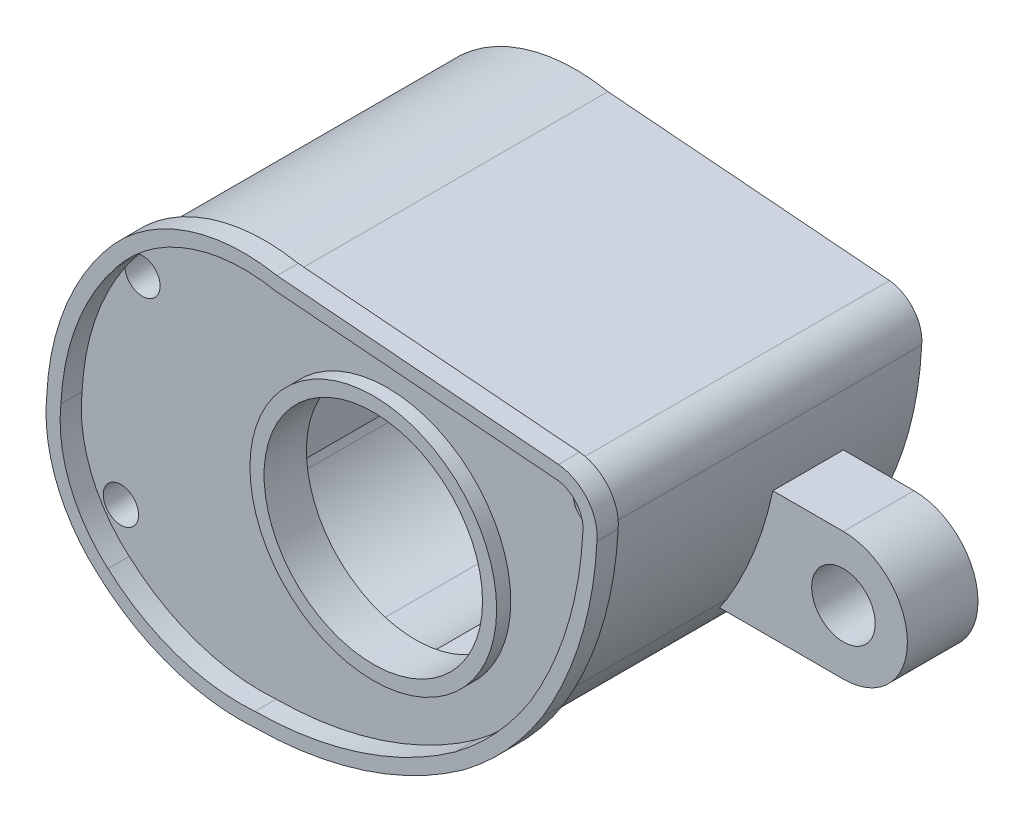
SolidWorks part; units mm, degrees
ref_plane "Front Plane" through (0, 0, 0) normal (0, 0, 1) x (1, 0, 0)
ref_plane "Top Plane" through (0, 0, 0) normal (0, 1, 0) x (1, 0, 0)
ref_plane "Right Plane" through (0, 0, 0) normal (1, 0, 0) x (0, 0, -1)
sketch "Sketch5" plane through (0, 0, 0) normal (0, 0, 1) x (1, 0, 0)
  line L0 (32.2567, 28.3094) -> (-7.6439, 31.5413)
  arc A0 (-7.6439, 31.5413) -> (-31.2267, 22.5712) centre (-12.2121, 8.0664) ccw
  arc A1 (-31.2267, 22.5712) -> (-39.1267, 1.5854) centre (-2.4724, -0.2331) ccw
  arc A2 (-39.1267, 1.5854) -> (-32.1216, -16.1277) centre (-18.7412, -0.5944) ccw
  arc A3 (-32.1216, -16.1277) -> (-10.5935, -23.4924) centre (-12.7582, 5.3271) ccw
  arc A4 (-10.5935, -23.4924) -> (18.3058, -14.101) centre (-11.0051, 26.9339) ccw
  arc A5 (18.3058, -14.101) -> (29.2221, -2.2809) centre (-8.5159, 21.6209) ccw
  arc A6 (29.2221, -2.2809) -> (36.8072, 22.6664) centre (-16.6755, 25.3008) ccw
  arc A7 (36.8072, 22.6664) -> (32.2567, 28.3094) centre (31.7105, 23.2127) ccw
  circle A8 centre (5.125, 6.1357) radius 15.4733
extrude "Boss-Extrude2" add sketch "Sketch5" along normal blind 44
sketch "Sketch12" plane through (0, 0, 44) normal (0, 0, 1) x (1, 0, 0)
  circle A3 centre (5.125, 6.1357) radius 15.4733
  circle A4 centre (5.125, 6.1357) radius 15.4733
  dimension "D1" = 0
extrude "Extrude-Thin3" add sketch "Sketch12" along normal blind 2 thin
sketch "Sketch16" plane through (0, 0, 0) normal (0, 0, -1) x (-1, 0, 0)
  line L43 (22.1955, 22.9487) -> (21.1955, 24.9487)
  line L44 (22.1955, 20.9487) -> (22.1955, 22.9487)
  line L45 (22.5955, 14.9487) -> (22.1955, 20.9487)
  line L46 (23.3698, 11.8701) -> (22.5955, 14.9487)
  line L47 (24.1112, 7.8732) -> (23.3698, 11.8701)
  line L48 (24.5555, 3.8743) -> (24.1112, 7.8732)
  line L49 (25.5954, -10.0513) -> (24.5555, 3.8743)
  line L50 (-15.5531, -13.0513) -> (-4.0536, -13.0513)
  line L51 (-25.5527, 9.9487) -> (-15.5531, -13.0513)
  line L52 (-29.6312, 9.9487) -> (-25.5527, 9.9487)
  line L53 (-31.5525, 24.9487) -> (-31.5525, 12.6882)
  line L54 (21.1955, 24.9487) -> (-31.5525, 24.9487)
  arc A12 (25.1918, -11.0133) -> (25.5954, -10.0513) centre (19.3606, -8.0014) ccw
  arc A13 (25.1918, -11.0133) -> (10.4852, -20.0276) centre (10.3895, -3.3677) cw
  arc A14 (-4.0536, -13.0513) -> (10.4852, -20.0276) centre (8.991, -4.5038) ccw
  arc A15 (-31.5525, 12.6882) -> (-29.6312, 9.9487) centre (-38.2464, 5.95) cw
extrude "Cut-Extrude1" cut sketch "Sketch16" against normal blind 40
sketch "Sketch20" plane through (0, 0, 44) normal (0, 0, 1) x (1, 0, 0)
  circle A0 centre (33.9607, 23.4641) radius 2.5
  circle A1 centre (-29.5785, 19.9554) radius 2.5
  circle A2 centre (-32.6296, -9.6403) radius 2.5
  point P2 (33.9607, 23.4641)
extrude "Cut-Extrude4" cut sketch "Sketch20" against normal blind 5
sketch "Sketch21" plane through (0, 0, 39) normal (0, 0, 1) x (1, 0, 0)
  circle A0 centre (33.9607, 23.4641) radius 1.5
  circle A2 centre (-29.5785, 19.9554) radius 1.5
  circle A3 centre (-32.6296, -9.6403) radius 1.5
extrude "Cut-Extrude5" cut sketch "Sketch21" against normal blind 10
sketch "Sketch22" plane through (0, 0, 44) normal (0, 0, 1) x (1, 0, 0)
  line L3 (32.1624, 27.3138) -> (-7.7808, 30.5492)
  line L4 (32.1624, 27.3138) -> (-7.7808, 30.5492)
  arc A24 (35.8099, 22.7457) -> (32.1624, 27.3138) centre (31.7105, 23.2127) ccw
  arc A25 (-7.7808, 30.5492) -> (-30.4373, 21.9572) centre (-12.2121, 8.0664) ccw
  arc A26 (-30.4373, 21.9572) -> (-38.1294, 1.5073) centre (-2.4724, -0.2331) ccw
  arc A27 (-38.1294, 1.5073) -> (-31.4602, -15.3776) centre (-18.7412, -0.5944) ccw
  arc A28 (-31.4602, -15.3776) -> (-10.6352, -22.4927) centre (-12.7582, 5.3271) ccw
  arc A29 (-10.6352, -22.4927) -> (17.7148, -13.2941) centre (-11.0051, 26.9339) ccw
  arc A30 (17.7148, -13.2941) -> (28.371, -1.7558) centre (-8.5159, 21.6209) ccw
  arc A31 (28.371, -1.7558) -> (35.8099, 22.7457) centre (-16.6755, 25.3008) ccw
  arc A32 (35.8099, 22.7457) -> (32.1624, 27.3138) centre (31.7105, 23.2127) ccw
  arc A33 (-7.7808, 30.5492) -> (-30.4373, 21.9572) centre (-12.2121, 8.0664) ccw
  arc A34 (-30.4373, 21.9572) -> (-38.1294, 1.5073) centre (-2.4724, -0.2331) ccw
  arc A35 (-38.1294, 1.5073) -> (-31.4602, -15.3776) centre (-18.7412, -0.5944) ccw
  arc A36 (-31.4602, -15.3776) -> (-10.6352, -22.4927) centre (-12.7582, 5.3271) ccw
  arc A37 (-10.6352, -22.4927) -> (17.7148, -13.2941) centre (-11.0051, 26.9339) ccw
  arc A38 (17.7148, -13.2941) -> (28.371, -1.7558) centre (-8.5159, 21.6209) ccw
  arc A39 (28.371, -1.7558) -> (35.8099, 22.7457) centre (-16.6755, 25.3008) ccw
  dimension "D1" = 1
extrude "Extrude-Thin4" add sketch "Sketch22" along normal blind 3 thin
ref_plane "Plane1" through (0, 0, 20) normal (0, 0, 1) x (1, 0, 0)
sketch "Sketch25" plane through (0, 0, 20) normal (0, 0, 1) x (1, 0, 0)
  line L0 (45.722, 14.2627) -> (35.722, 14.2627)
  line L1 (45.722, -3.8644) -> (28.1713, -3.8644)
  circle A3 centre (45.722, 5.1991) radius 4.5
  arc A4 (18.3058, -14.101) -> (29.2221, -2.2809) centre (-8.5159, 21.6209) ccw construction
  circle A5 centre (45.722, 5.1991) radius 9.0635
  arc A7 (29.2221, -2.2809) -> (36.8072, 22.6664) centre (-16.6755, 25.3008) ccw construction
  arc A8 (35.722, 14.2627) -> (28.1713, -3.8644) centre (-17.3042, 25.7142) cw
extrude "Boss-Extrude4" add sketch "Sketch25" against normal blind 10 separate body contours A5 | A3
sketch "Sketch26" plane through (0, 0, 20) normal (0, 0, 1) x (1, 0, 0)
  line L2 (45.722, 14.2627) -> (35.722, 14.2627)
  line L3 (45.722, -3.8644) -> (28.1713, -3.8644)
  circle A5 centre (45.722, 5.1991) radius 9.0635 construction
  arc A6 (29.2221, -2.2809) -> (36.8072, 22.6664) centre (-16.6755, 25.3008) ccw construction
  arc A7 (18.3058, -14.101) -> (29.2221, -2.2809) centre (-8.5159, 21.6209) ccw construction
  arc A8 (35.722, 14.2627) -> (28.1713, -3.8644) centre (-16.0293, 25.1832) cw
  arc A9 (45.722, 14.2627) -> (45.722, -3.8644) centre (45.722, 5.1991) ccw
extrude "Boss-Extrude5" add sketch "Sketch26" against normal blind 10
